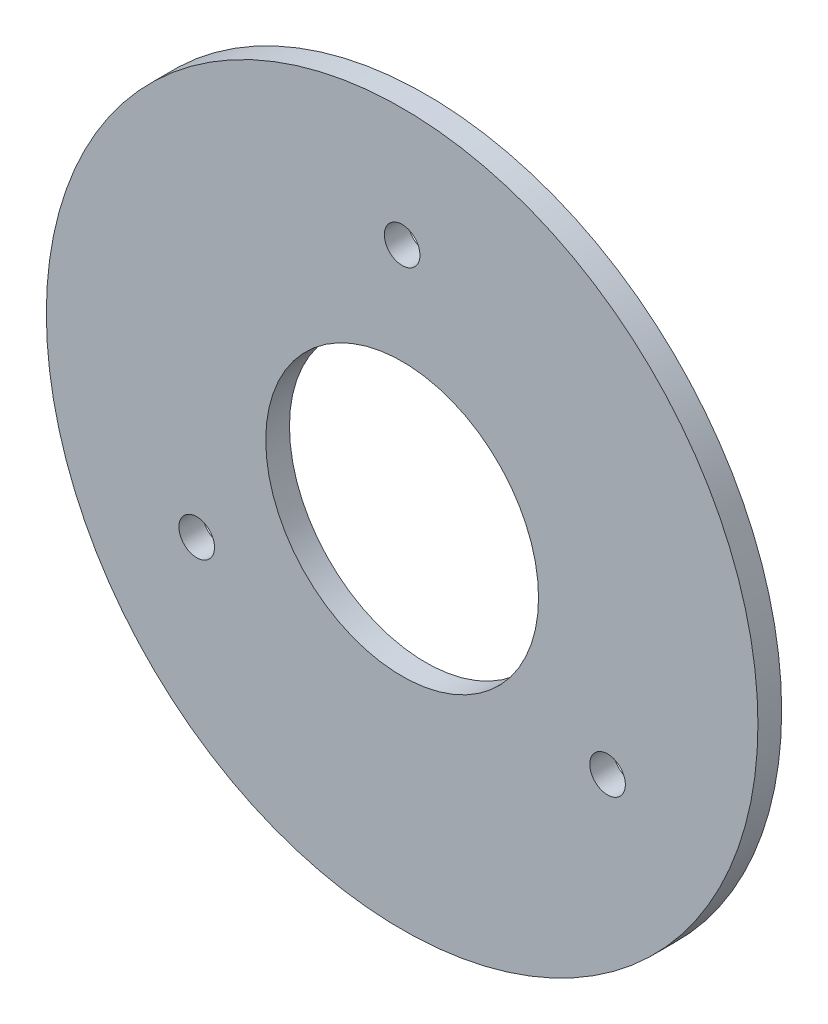
SolidWorks part; units mm, degrees
ref_plane "前视基准面" through (0, 0, 0) normal (0, 0, 1) x (1, 0, 0)
ref_plane "上视基准面" through (0, 0, 0) normal (0, 1, 0) x (1, 0, 0)
ref_plane "右视基准面" through (0, 0, 0) normal (1, 0, 0) x (0, 0, -1)
other "Configuration Table"
sketch "草图1" plane through (0, 0, 0) normal (0, 0, 1) x (1, 0, 0)
  circle A0 centre (0, 0) radius 30
  circle A1 centre (0, 0) radius 11.5
  circle A2 centre (0, 20) radius 1.5
  circle A3 centre (17.3205, -10) radius 1.5
  circle A4 centre (-17.3205, -10) radius 1.5
  point P7 (-17.5437, -13.4833)
  point P8 (0, 0)
  point P12 (0, 0)
  dimension "D1" = 23
  dimension "D2" = 60
  dimension "D3" = 3
  dimension "D4" = 20
  dimension "D5" = 3
extrude "凸台-拉伸1" add sketch "草图1" along normal blind 2
